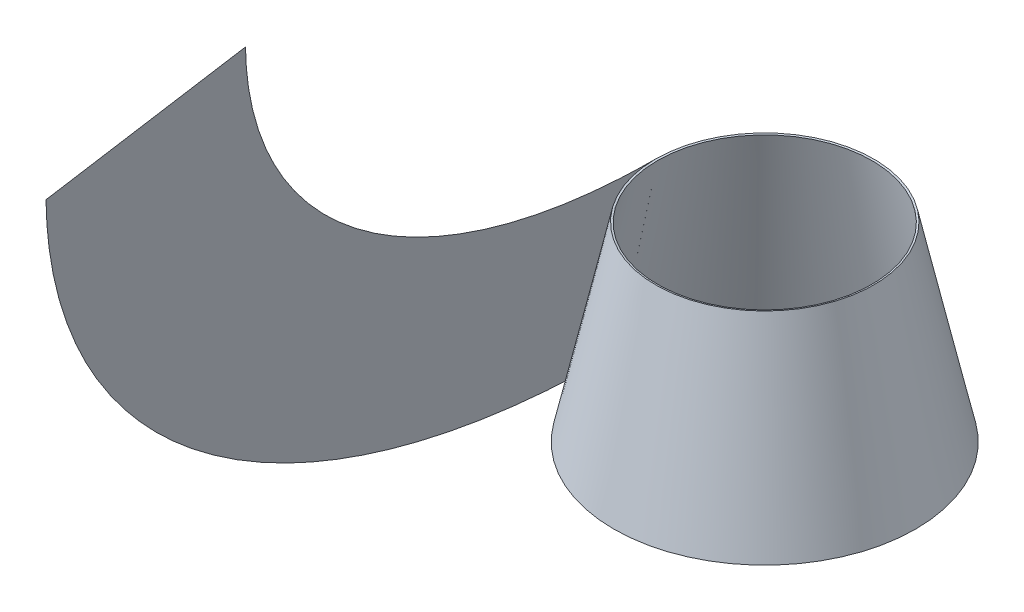
SolidWorks part; units mm, degrees
ref_plane "Front Plane" through (0, 0, 0) normal (0, 0, 1) x (1, 0, 0)
ref_plane "Top Plane" through (0, 0, 0) normal (0, 1, 0) x (1, 0, 0)
ref_plane "Right Plane" through (0, 0, 0) normal (1, 0, 0) x (0, 0, -1)
sketch "Sketch1" plane through (0, 0, 0) normal (0, 0, 1) x (1, 0, 0)
  line L0 (-33.8636, 0) -> (-24.35, 43.25)
  line L1 (-33.8636, 0) -> (-34.2853, 0.0928)
  line L2 (-24.35, 43.25) -> (-24.7717, 43.3428)
  line L3 (-34.2853, 0.0928) -> (-24.7717, 43.3428)
  line L4 (0, 0) -> (0, 38.0052) construction
  dimension "D1" = 0.4318
  dimension "D2" = 43.25
  dimension "D3" = 33.8636
  dimension "D4" = 24.35
revolve "Revolve1" add sketch "Sketch1" angle 359.99 about L4
surface "Surface-Flatten1"
